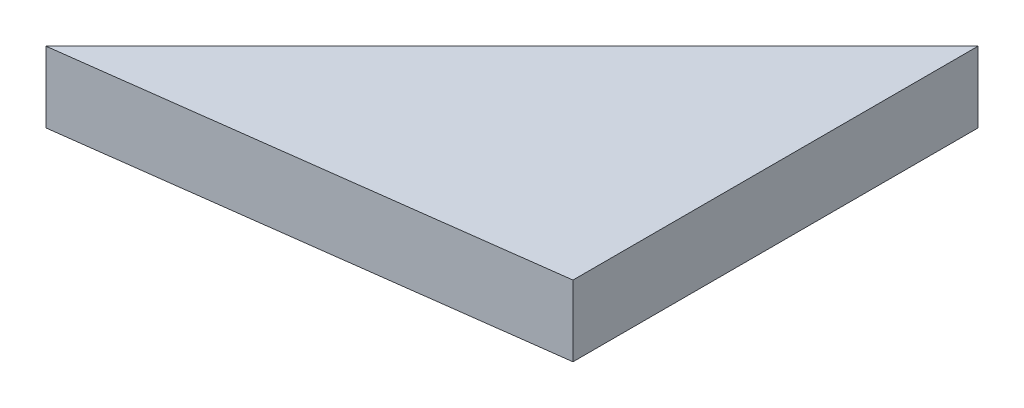
SolidWorks part; units mm, degrees
ref_plane "Front Plane" through (0, 0, 0) normal (0, 0, 1) x (1, 0, 0)
ref_plane "Top Plane" through (0, 0, 0) normal (0, 1, 0) x (1, 0, 0)
ref_plane "Right Plane" through (0, 0, 0) normal (1, 0, 0) x (0, 0, -1)
sketch "Sketch1" plane through (0, 0, 0) normal (0, 1, 0) x (1, 0, 0)
  line L0 (0, 0) -> (0, 18.1605)
  line L1 (0, 18.1605) -> (-20.8947, -2.7341)
  line L2 (0, 0) -> (-20.8947, -2.7341)
  dimension "D1" = 45
  dimension "D2" = 97.455
extrude "Boss-Extrude1" add sketch "Sketch1" along normal blind 3.175
